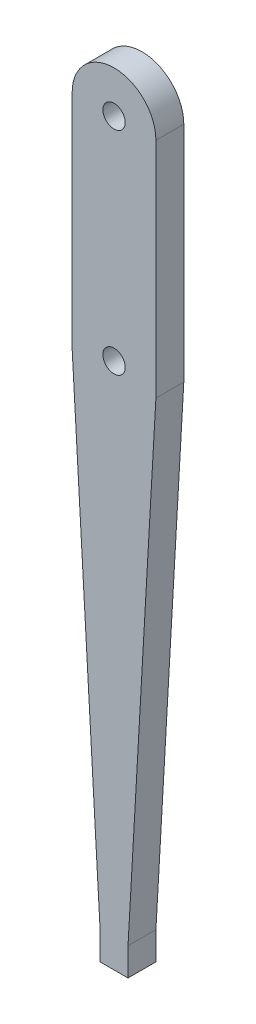
SolidWorks part; units mm, degrees
ref_plane "Alzado" through (0, 0, 0) normal (0, 0, 1) x (1, 0, 0)
ref_plane "Planta" through (0, 0, 0) normal (0, 1, 0) x (1, 0, 0)
ref_plane "Vista lateral" through (0, 0, 0) normal (1, 0, 0) x (0, 0, -1)
sketch "Croquis1" plane through (0, 0, 0) normal (0, 0, 1) x (1, 0, 0)
  line L0 (-7.5, -40) -> (-7.5, 0)
  line L1 (-2.4997, -132.5) -> (2.4997, -132.5)
  line L2 (7.5, 0) -> (7.5, -40)
  line L3 (-2.4997, -132.5) -> (-2.4997, -127.5)
  line L4 (-7.5, -40) -> (-2.4997, -127.5)
  line L5 (2.4997, -132.5) -> (2.4997, -127.5)
  line L6 (0, 7.5) -> (-66.1869, 7.5) construction
  line L8 (7.5, -40) -> (2.4997, -127.5)
  arc A1 (7.5, 0) -> (-7.5, 0) centre (0, 0) ccw
  circle A2 centre (0, -38) radius 2
  circle A3 centre (0, 0) radius 2
  dimension "D2" = 15
  dimension "D4" = 38
  dimension "D5" = 4
  dimension "D9" = 4
  dimension "D3" = 5
  dimension "D6" = 40
  dimension "D7" = 140
  dimension "D8" = 5
  dimension "D10" = 0
extrude "Saliente-Extruir5" add sketch "Croquis1" along normal blind 5
